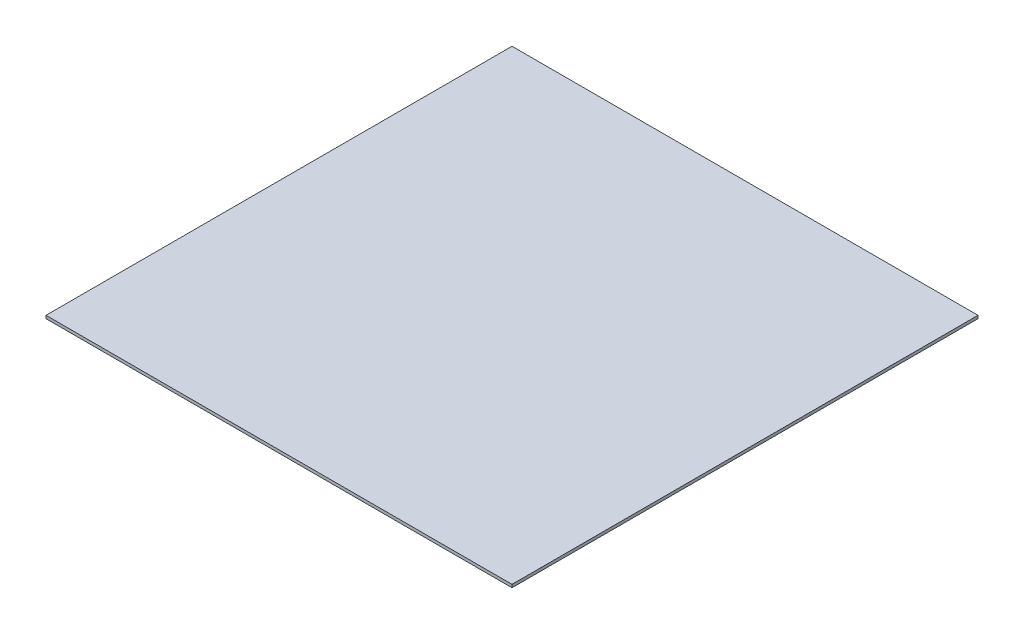
SolidWorks part; units mm, degrees
ref_plane "Front Plane" through (0, 0, 0) normal (0, 0, 1) x (1, 0, 0)
ref_plane "Top Plane" through (0, 0, 0) normal (0, 1, 0) x (1, 0, 0)
ref_plane "Right Plane" through (0, 0, 0) normal (1, 0, 0) x (0, 0, -1)
sketch "Sketch1" plane through (0, 0, 0) normal (0, 1, 0) x (1, 0, 0)
  line L1 (0, 0) -> (1000, 0)
  line L2 (0, 0) -> (0, 1000)
  line L3 (0, 1000) -> (1000, 1000)
  line L4 (1000, 0) -> (1000, 1000)
  dimension "D1" = 1000
  dimension "D2" = 1000
extrude "Boss-Extrude1" add sketch "Sketch1" along normal blind 6.35
